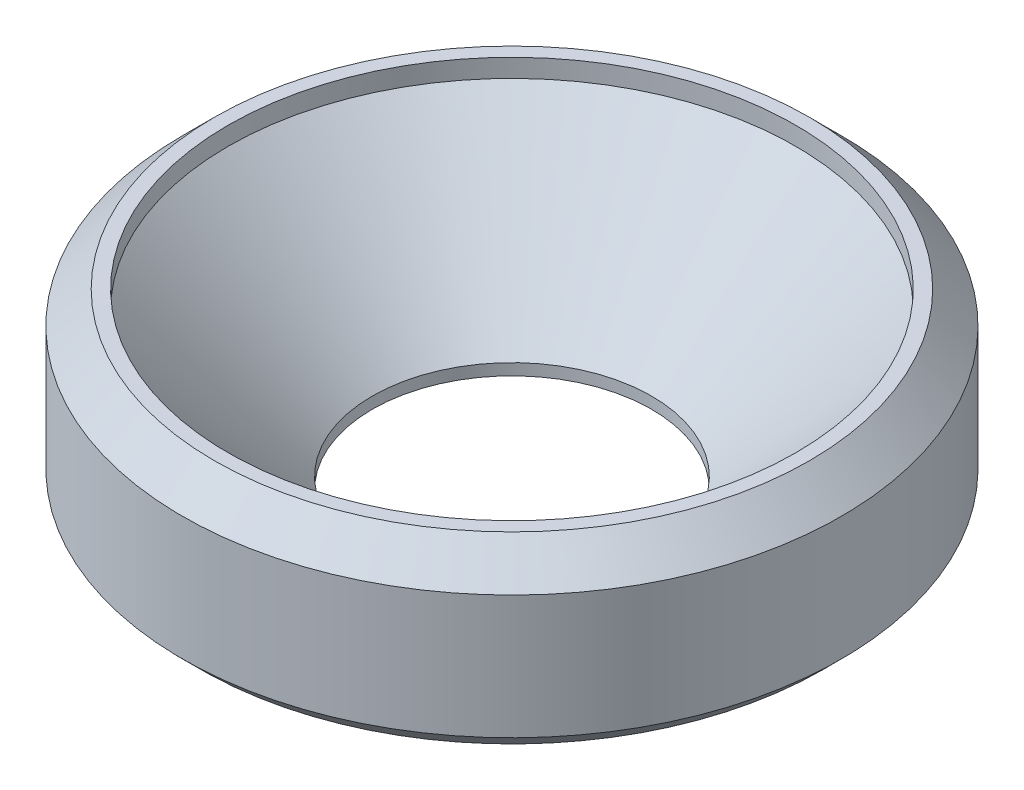
SolidWorks part; units mm, degrees
ref_plane "Front Plane" through (0, 0, 0) normal (0, 0, 1) x (1, 0, 0)
ref_plane "Top Plane" through (0, 0, 0) normal (0, 1, 0) x (1, 0, 0)
ref_plane "Right Plane" through (0, 0, 0) normal (1, 0, 0) x (0, 0, -1)
sketch "Sketch1" plane through (0, 0, 0) normal (0, 0, 1) x (1, 0, 0)
  line L0 (-6.8, 0) -> (-3.05, 0)
  line L1 (-6.8, 0) -> (-7.2, 0.4)
  line L2 (-7.2, 0.4) -> (-7.2, 3.1)
  line L3 (-7.2, 3.1) -> (-6.5, 3.8)
  line L4 (-6.5, 3.8) -> (-6.2, 3.8)
  line L5 (-6.2, 3.8) -> (-6.2, 3.4)
  line L6 (-6.2, 3.4) -> (-3.05, 0.25)
  line L7 (-3.05, 0) -> (-3.05, 0.25)
  line L8 (0, 35.7053) -> (0, -10.7314) construction
  point P11 (-5.2244, 5.5225)
  point P13 (0, 0)
  point P15 (-5.068, 3.2)
  point P16 (0, 0)
  dimension "D1" = 14.4
  dimension "D2" = 6.1
  dimension "D3" = 45
  dimension "D4" = 0.4
  dimension "D5" = 0.4
  dimension "D6" = 3.8
  dimension "D7" = 12.4
  dimension "D8" = 0.7
revolve "Revolve1" add sketch "Sketch1" angle 360 about L8
